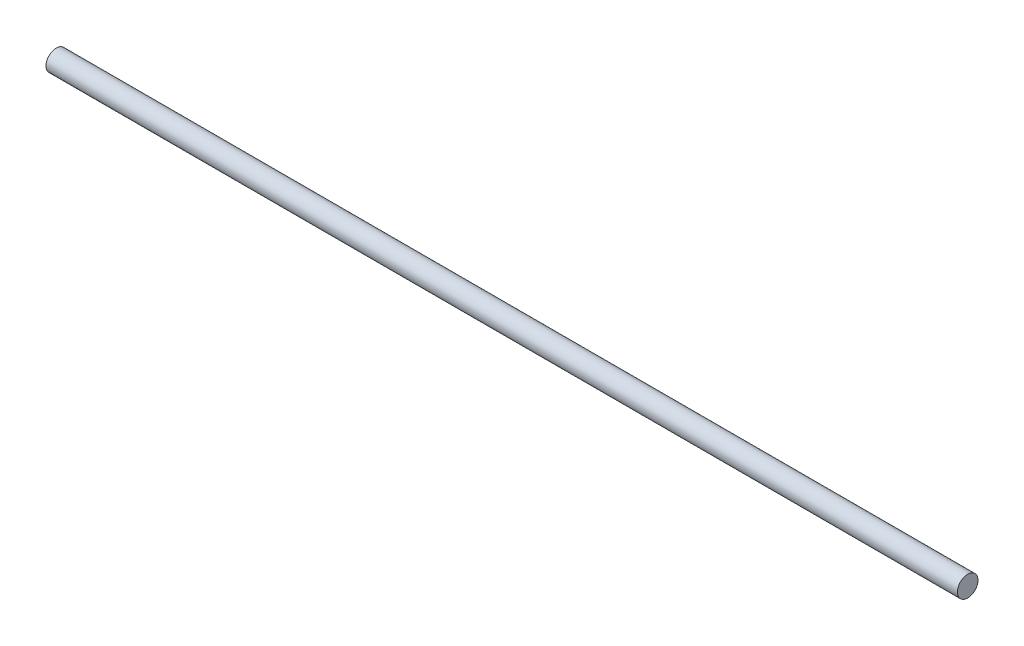
SolidWorks part; units mm, degrees
material "Zoltek Panex 33"
ref_plane "Front Plane" through (0, 0, 0) normal (0, 0, 1) x (1, 0, 0)
ref_plane "Top Plane" through (0, 0, 0) normal (0, 1, 0) x (1, 0, 0)
ref_plane "Right Plane" through (0, 0, 0) normal (1, 0, 0) x (0, 0, -1)
sketch "Sketch1" plane through (0, 0, 0) normal (1, 0, 0) x (0, 0, -1)
  circle A0 centre (0, 0) radius 9
  dimension "D1" = 18
extrude "Boss-Extrude1" add sketch "Sketch1" along normal mid plane 796
